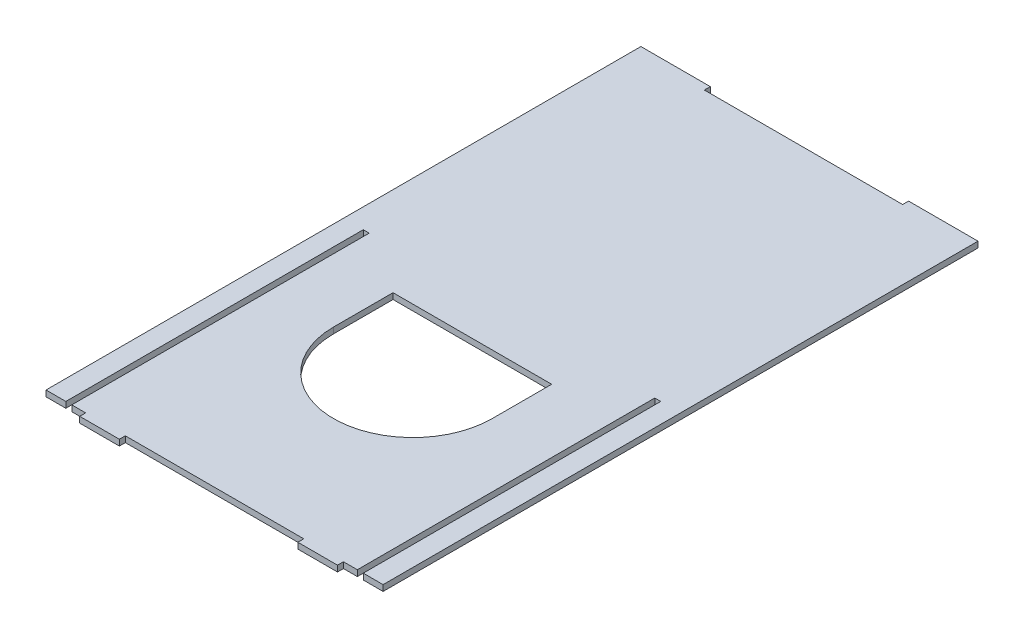
SolidWorks part; units mm, degrees
ref_plane "Front Plane" through (0, 0, 0) normal (0, 0, 1) x (1, 0, 0)
ref_plane "Top Plane" through (0, 0, 0) normal (0, 1, 0) x (1, 0, 0)
ref_plane "Right Plane" through (0, 0, 0) normal (1, 0, 0) x (0, 0, -1)
sketch "Sketch1" plane through (0, 0, 0) normal (0, 1, 0) x (1, 0, 0)
  line L0 (300, 0) -> (300, -6)
  line L2 (0, 0) -> (0, 600)
  line L3 (0, 600) -> (340, 600)
  line L4 (340, 0) -> (340, 600)
  line L5 (300, -6) -> (260, -6)
  line L6 (260, -6) -> (260, 0)
  line L7 (40, 0) -> (40, -6)
  line L8 (40, -6) -> (80, -6)
  line L9 (80, -6) -> (80, 0)
  line L10 (40, 0) -> (0, 0)
  line L11 (80, 0) -> (260, 0)
  line L12 (300, 0) -> (340, 0)
  point P11 (80, -3)
  dimension "D1" = 340
  dimension "D2" = 600
  dimension "D3" = 40
  dimension "D4" = 6
  dimension "D5" = 40
  dimension "D6" = 180
extrude "Boss-Extrude1" add sketch "Sketch1" along normal blind 6
sketch "Sketch2" plane through (0, 6, 0) normal (0, 1, 0) x (1, 0, 0)
  line L1 (20, 0) -> (26, 0)
  line L2 (20, 0) -> (20, 300)
  line L3 (20, 300) -> (26, 300)
  line L4 (26, 0) -> (26, 300)
  line L5 (0, 600) -> (0, 0) construction
  line L6 (0, 0) -> (40, 0) construction
  line L7 (0, 0) -> (40, 0) construction
  dimension "D1" = 300
  dimension "D2" = 6
  dimension "D3" = 20
extrude "Cut-Extrude1" cut sketch "Sketch2" against normal blind 6
pattern_linear "LPattern1" count 2 spacing 294 along (1, 0, 0) of "Cut-Extrude1"
sketch "Sketch3" plane through (0, 6, 0) normal (0, 1, 0) x (1, 0, 0)
  line L0 (90, 200) -> (90, 260)
  line L3 (340, 600) -> (0, 600) construction
  line L4 (70, 600) -> (270, 600)
  line L5 (70, 600) -> (70, 594)
  line L6 (70, 594) -> (270, 594)
  line L7 (270, 600) -> (270, 594)
  line L9 (250, 200) -> (250, 260)
  line L10 (90, 260) -> (250, 260)
  line L12 (0, 600) -> (0, 0) construction
  line L13 (80, 0) -> (260, 0) construction
  arc A1 (90, 200) -> (250, 200) centre (170, 200) ccw
  point P5 (170, 120)
  point P14 (170, 600)
  dimension "D1" = 200
  dimension "D2" = 80
  dimension "D4" = 170
  dimension "D6" = 160
  dimension "D5" = 6
  dimension "D7" = 120
  dimension "D8" = 60
extrude "Cut-Extrude2" cut sketch "Sketch3" against normal blind 6
